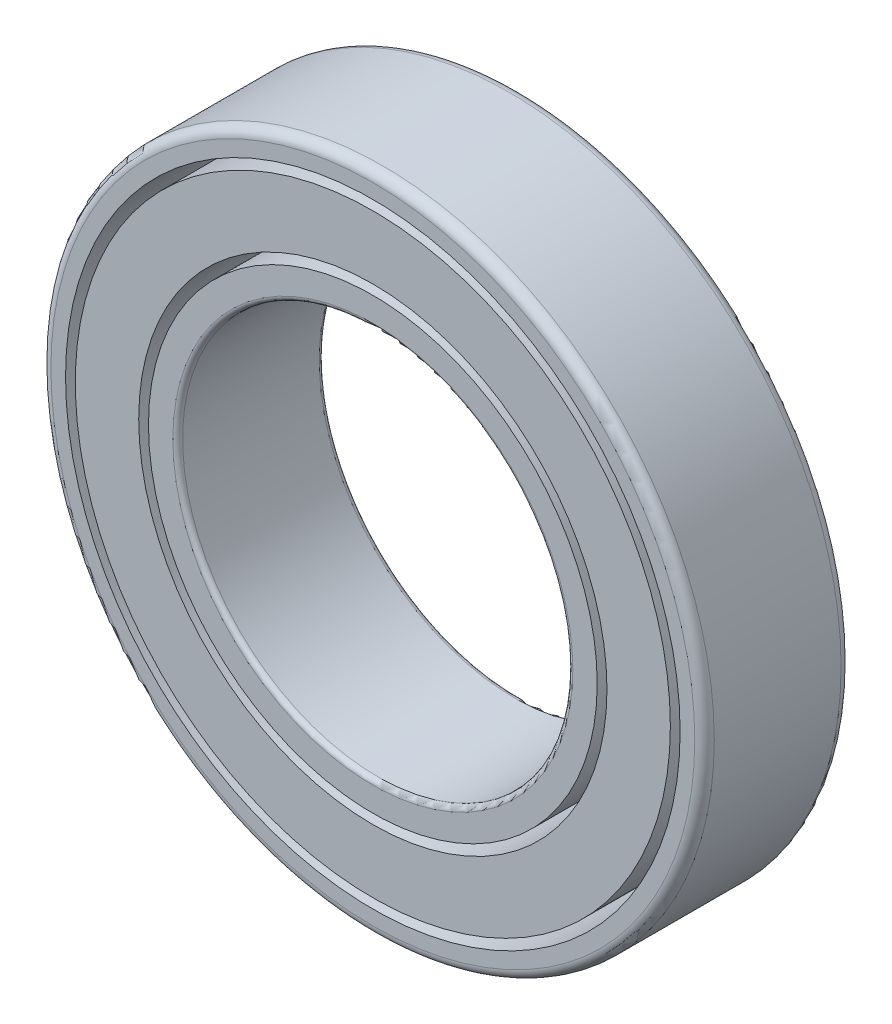
SolidWorks part; units mm, degrees
material "AISI 304"
ref_plane "Alzado" through (0, 0, 0) normal (0, 0, 1) x (1, 0, 0)
ref_plane "Planta" through (0, 0, 0) normal (0, 1, 0) x (1, 0, 0)
ref_plane "Vista lateral" through (0, 0, 0) normal (1, 0, 0) x (0, 0, -1)
sketch "Croquis1" plane through (0, 0, 0) normal (0, 0, 1) x (1, 0, 0)
  circle A0 centre (0, 0) radius 20
  circle A1 centre (0, 0) radius 31.5
  circle A2 centre (0, 0) radius 23
  circle A3 centre (0, 0) radius 24
  circle A4 centre (0, 0) radius 30.5
  circle A5 centre (0, 0) radius 34
  dimension "D1" = 40
  dimension "D2" = 61
  dimension "D3" = 46
  dimension "D4" = 48
  dimension "D5" = 63
  dimension "D6" = 68
extrude "Saliente-Extruir1" add sketch "Croquis1" along normal mid plane 15 contours A4 A3 | A2 A0 | A5 | A1
fillet "Redondeo1" radius 1 2 edges at (34, 0, -7.5) (34, 0, 7.5)
fillet "Redondeo2" radius 0.5 2 edges at (20, 0, -7.5) (20, 0, 7.5)
